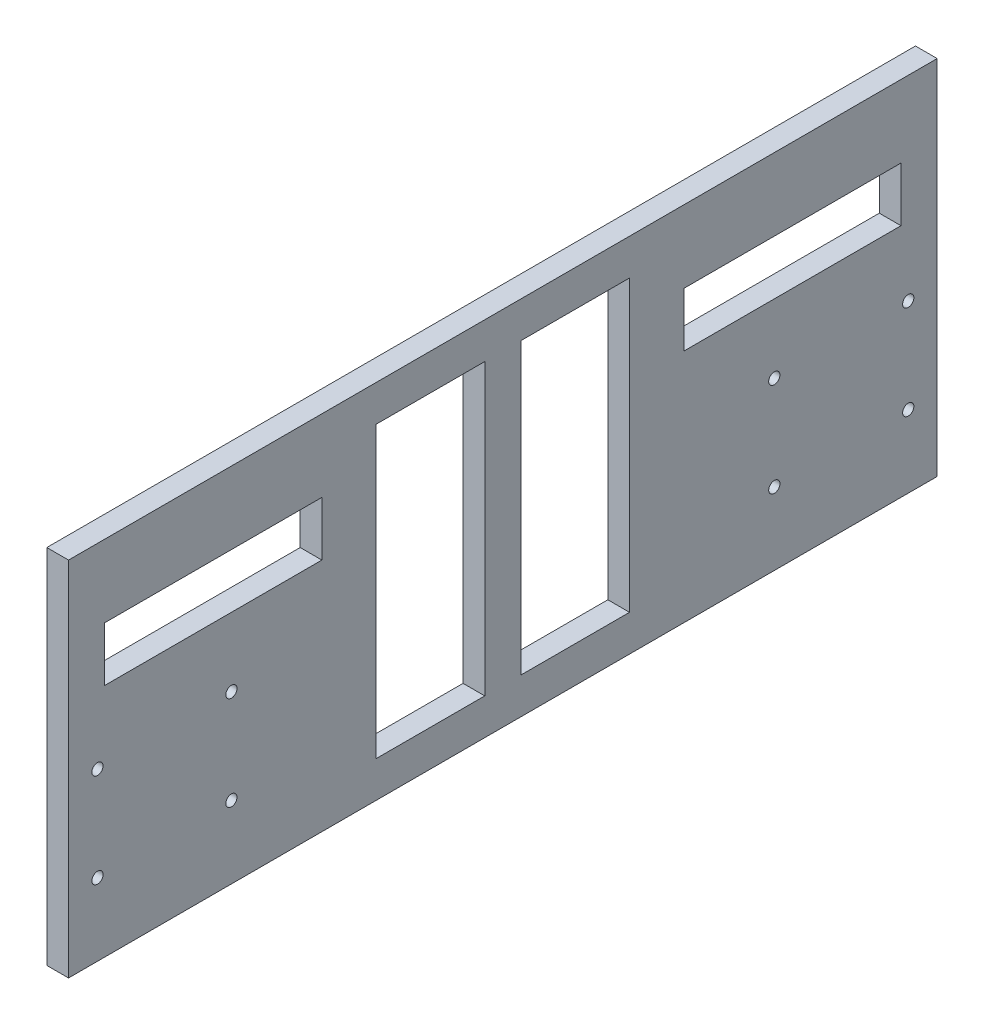
SolidWorks part; units mm, degrees
ref_plane "前视基准面" through (0, 0, 0) normal (0, 0, 1) x (1, 0, 0)
ref_plane "上视基准面" through (0, 0, 0) normal (0, 1, 0) x (1, 0, 0)
ref_plane "右视基准面" through (0, 0, 0) normal (1, 0, 0) x (0, 0, -1)
sketch "草图1" plane through (0, 0, 0) normal (1, 0, 0) x (0, 0, -1)
  line L1 (0, 0) -> (240, 0)
  line L2 (0, 0) -> (0, -100)
  line L3 (0, -100) -> (240, -100)
  line L4 (240, 0) -> (240, -100)
  dimension "D1" = 240
  dimension "D2" = 100
extrude "凸台-拉伸1" add sketch "草图1" along normal blind 6
sketch "草图2" plane through (6, 0, 0) normal (1, 0, 0) x (0, 0, -1)
  line L0 (0, 0) -> (0, -100) construction
  line L1 (8, -54) -> (45, -54) construction
  line L2 (8, -54) -> (8, -80) construction
  line L3 (8, -80) -> (45, -80) construction
  line L4 (45, -54) -> (45, -80) construction
  line L5 (240, 0) -> (0, 0) construction
  line L6 (120, 0) -> (120, -100) construction
  line L7 (0, -100) -> (240, -100) construction
  line L8 (195, -54) -> (195, -80) construction
  line L9 (232, -80) -> (195, -80) construction
  line L10 (232, -54) -> (232, -80) construction
  line L11 (232, -54) -> (195, -54) construction
  circle A0 centre (8, -54) radius 1.55
  circle A1 centre (45, -80) radius 1.55
  circle A2 centre (45, -54) radius 1.55
  circle A3 centre (8, -80) radius 1.55
  circle A4 centre (232, -80) radius 1.55
  circle A5 centre (195, -54) radius 1.55
  circle A6 centre (195, -80) radius 1.55
  circle A7 centre (232, -54) radius 1.55
  dimension "D5" = 3.1
  dimension "D1" = 8
  dimension "D2" = 54
  dimension "D3" = 37
  dimension "D4" = 26
extrude "切除-拉伸1" cut sketch "草图2" against normal through all
sketch "草图3" plane through (6, 0, 0) normal (1, 0, 0) x (0, 0, -1)
  line L0 (120, 0) -> (120, -100) construction
  line L1 (10, -20) -> (70, -20)
  line L2 (10, -20) -> (10, -35)
  line L3 (10, -35) -> (70, -35)
  line L4 (70, -20) -> (70, -35)
  line L5 (240, 0) -> (0, 0) construction
  line L6 (0, -100) -> (240, -100) construction
  line L7 (0, 0) -> (0, -100) construction
  line L8 (170, -20) -> (170, -35)
  line L9 (230, -35) -> (170, -35)
  line L10 (230, -20) -> (230, -35)
  line L11 (230, -20) -> (170, -20)
  dimension "D1" = 10
  dimension "D2" = 20
  dimension "D3" = 15
  dimension "D4" = 60
extrude "切除-拉伸2" cut sketch "草图3" against normal through all
sketch "草图4" plane through (6, 0, 0) normal (1, 0, 0) x (0, 0, -1)
  line L0 (120, 0) -> (120, -100) construction
  line L1 (85, -10) -> (115, -10)
  line L2 (85, -10) -> (85, -90)
  line L3 (85, -90) -> (115, -90)
  line L4 (115, -10) -> (115, -90)
  line L5 (240, 0) -> (0, 0) construction
  line L6 (0, -100) -> (240, -100) construction
  line L7 (0, 0) -> (0, -100) construction
  line L8 (125, -10) -> (125, -90)
  line L9 (155, -90) -> (125, -90)
  line L10 (155, -10) -> (155, -90)
  line L11 (155, -10) -> (125, -10)
  dimension "D1" = 10
  dimension "D2" = 10
  dimension "D3" = 85
  dimension "D4" = 30
extrude "切除-拉伸3" cut sketch "草图4" against normal through all contours L4 L1 L2 L3 | L8 L9 L10 L11
sketch "草图5" plane through (0, 0, 0) normal (-1, 0, 0) x (0, 0, 1)
  circle A0 centre (-195, -80) radius 3
  circle A1 centre (-232, -80) radius 3
  circle A2 centre (-195, -54) radius 3
  circle A3 centre (-232, -54) radius 3
  circle A4 centre (-45, -80) radius 3
  circle A5 centre (-8, -80) radius 3
  circle A6 centre (-8, -54) radius 3
  circle A7 centre (-45, -54) radius 3
  dimension "D1" = 6
extrude "切除-拉伸4" cut sketch "草图5" against normal blind 3
